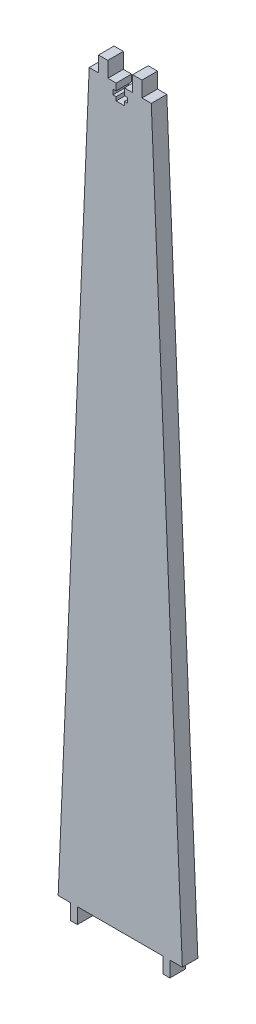
SolidWorks part; units mm, degrees
ref_plane "Front Plane" through (0, 0, 0) normal (0, 0, 1) x (1, 0, 0)
ref_plane "Top Plane" through (0, 0, 0) normal (0, 1, 0) x (1, 0, 0)
ref_plane "Right Plane" through (0, 0, 0) normal (1, 0, 0) x (0, 0, -1)
sketch "Sketch1" plane through (0, 0, 0) normal (0, 0, 1) x (1, 0, 0)
  line L1 (25.4, 0) -> (12.7, 299.72)
  line L3 (-12.7, 299.72) -> (-25.4, 0)
  line L4 (0, 0) -> (0, 299.72) construction
  line L5 (-25.4, 0) -> (-20.32, 0)
  line L6 (-20.32, 0) -> (-20.32, -6.35)
  line L7 (-20.32, -6.35) -> (-17.526, -6.35)
  line L8 (-17.526, -6.35) -> (-17.526, 0)
  line L9 (-17.526, 0) -> (17.526, 0)
  line L10 (25.4, 0) -> (20.32, 0)
  line L11 (17.526, -6.35) -> (17.526, 0)
  line L12 (20.32, -6.35) -> (17.526, -6.35)
  line L13 (20.32, 0) -> (20.32, -6.35)
  line L14 (8.89, 306.07) -> (8.89, 299.72)
  line L15 (-12.7, 299.72) -> (-8.89, 299.72)
  line L16 (-8.89, 306.07) -> (-5.08, 306.07)
  line L17 (-8.89, 306.07) -> (-8.89, 299.72)
  line L18 (-5.08, 306.07) -> (-5.08, 299.72)
  line L19 (-5.08, 299.72) -> (-1.7, 299.72)
  line L20 (-1.7, 299.72) -> (-1.7, 296.926)
  line L21 (-1.7, 296.926) -> (-2.97, 296.926)
  line L22 (-2.97, 296.926) -> (-2.97, 294.894)
  line L23 (12.7, 299.72) -> (8.89, 299.72)
  line L24 (-2.97, 294.894) -> (-1.7, 294.894)
  line L25 (8.89, 306.07) -> (5.08, 306.07)
  line L26 (5.08, 306.07) -> (5.08, 299.72)
  line L27 (5.08, 299.72) -> (1.7, 299.72)
  line L28 (1.7, 299.72) -> (1.7, 296.926)
  line L29 (1.7, 296.926) -> (2.97, 296.926)
  line L30 (2.97, 296.926) -> (2.97, 294.894)
  line L31 (2.97, 294.894) -> (1.7, 294.894)
  line L32 (1.7, 294.894) -> (1.7, 293.37)
  line L33 (1.7, 293.37) -> (-1.7, 293.37)
  line L34 (-1.7, 294.894) -> (-1.7, 293.37)
  point P37 (0, 293.37)
  dimension "D1" = 6.35
  dimension "D2" = 25.4
  dimension "D3" = 50.8
  dimension "D4" = 2.794
  dimension "D5" = 5.08
  dimension "D6" = 6.35
  dimension "D7" = 299.72
  dimension "D8" = 6.35
  dimension "D9" = 3.81
  dimension "D10" = 3.81
  dimension "D11" = 3.4
  dimension "D12" = 1.7
  dimension "D13" = 1.27
  dimension "D14" = 1.27
  dimension "D15" = 2.032
  dimension "D16" = 6.35
  dimension "D17" = 2.794
  dimension "D19" = 3.81
  dimension "D20" = 2.794
extrude "Boss-Extrude1" add sketch "Sketch1" along normal blind 6.35
